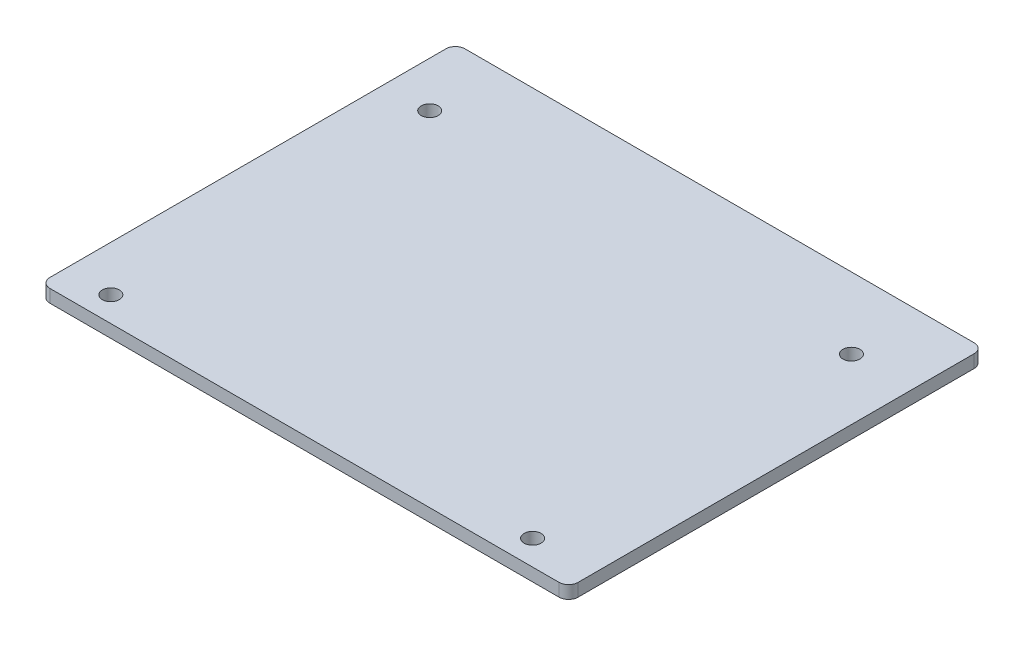
SolidWorks part; units mm, degrees
ref_plane "前视基准面" through (0, 0, 0) normal (0, 0, 1) x (1, 0, 0)
ref_plane "上视基准面" through (0, 0, 0) normal (0, 1, 0) x (1, 0, 0)
ref_plane "右视基准面" through (0, 0, 0) normal (1, 0, 0) x (0, 0, -1)
sketch "草图1" plane through (0, 0, 0) normal (0, 1, 0) x (1, 0, 0)
  line L1 (-51.5, -40.5) -> (51.5, -40.5)
  line L2 (-51.5, -40.5) -> (-51.5, 40.5)
  line L3 (-51.5, 40.5) -> (51.5, 40.5)
  line L4 (51.5, -40.5) -> (51.5, 40.5)
  line L5 (-51.5, -40.5) -> (51.5, 40.5) construction
  line L6 (-51.5, 40.5) -> (51.5, -40.5) construction
  point P0 (0, 0)
  dimension "D1" = 81
  dimension "D2" = 103
extrude "凸台-拉伸1" add sketch "草图1" along normal blind 2.5
fillet "圆角1" radius 2 4 edges at (51.5, 1.25, -40.5) (-51.5, 1.25, -40.5) (51.5, 1.25, 40.5) (-51.5, 1.25, 40.5)
sketch "草图2" plane through (0, 2.5, 0) normal (0, 1, 0) x (1, 0, 0)
  line L0 (49.5, 40.5) -> (-49.5, 40.5) construction
  line L1 (-42.5, 26.5) -> (39.5, 26.5) construction
  line L2 (-42.5, 26.5) -> (-42.5, -35.5) construction
  line L3 (-42.5, -35.5) -> (39.5, -35.5) construction
  line L4 (39.5, 26.5) -> (39.5, -35.5) construction
  line L5 (51.5, -38.5) -> (51.5, 38.5) construction
  circle A0 centre (-42.5, 26.5) radius 1.65
  circle A1 centre (39.5, 26.5) radius 1.65
  circle A2 centre (39.5, -35.5) radius 1.65
  circle A3 centre (-42.5, -35.5) radius 1.65
  dimension "D3" = 3.3
  dimension "D1" = 82
  dimension "D2" = 62
  dimension "D4" = 14
  dimension "D5" = 12
extrude "切除-拉伸1" cut sketch "草图2" against normal through all
sketch "草图3" plane through (0, 2.5, 0) normal (0, 1, 0) x (1, 0, 0)
  line L0 (49.5, 40.35) -> (-49.5, 40.35)
  line L1 (-51.35, 38.5) -> (-51.35, -38.5)
  line L2 (-49.5, -40.35) -> (49.5, -40.35)
  line L3 (51.35, -38.5) -> (51.35, 38.5)
  line L4 (49.5, 40.5) -> (-49.5, 40.5)
  line L5 (51.5, -38.5) -> (51.5, 38.5)
  line L6 (-49.5, -40.5) -> (49.5, -40.5)
  line L7 (-51.5, 38.5) -> (-51.5, -38.5)
  line L8 (49.5, 40.5) -> (-49.5, 40.5)
  line L9 (51.5, -38.5) -> (51.5, 38.5)
  line L10 (-49.5, -40.5) -> (49.5, -40.5)
  line L11 (-51.5, 38.5) -> (-51.5, -38.5)
  arc A0 (-49.5, 40.35) -> (-51.35, 38.5) centre (-49.5, 38.5) ccw
  arc A1 (-51.35, -38.5) -> (-49.5, -40.35) centre (-49.5, -38.5) ccw
  arc A2 (49.5, -40.35) -> (51.35, -38.5) centre (49.5, -38.5) ccw
  arc A3 (51.35, 38.5) -> (49.5, 40.35) centre (49.5, 38.5) ccw
  arc A4 (51.5, 38.5) -> (49.5, 40.5) centre (49.5, 38.5) ccw
  arc A5 (49.5, -40.5) -> (51.5, -38.5) centre (49.5, -38.5) ccw
  arc A6 (-51.5, -38.5) -> (-49.5, -40.5) centre (-49.5, -38.5) ccw
  arc A7 (-49.5, 40.5) -> (-51.5, 38.5) centre (-49.5, 38.5) ccw
  arc A8 (51.5, 38.5) -> (49.5, 40.5) centre (49.5, 38.5) ccw
  arc A9 (49.5, -40.5) -> (51.5, -38.5) centre (49.5, -38.5) ccw
  arc A10 (-51.5, -38.5) -> (-49.5, -40.5) centre (-49.5, -38.5) ccw
  arc A11 (-49.5, 40.5) -> (-51.5, 38.5) centre (-49.5, 38.5) ccw
  dimension "D1" = 0
  dimension "D2" = 0.15
extrude "切除-拉伸2" cut sketch "草图3" against normal through all
